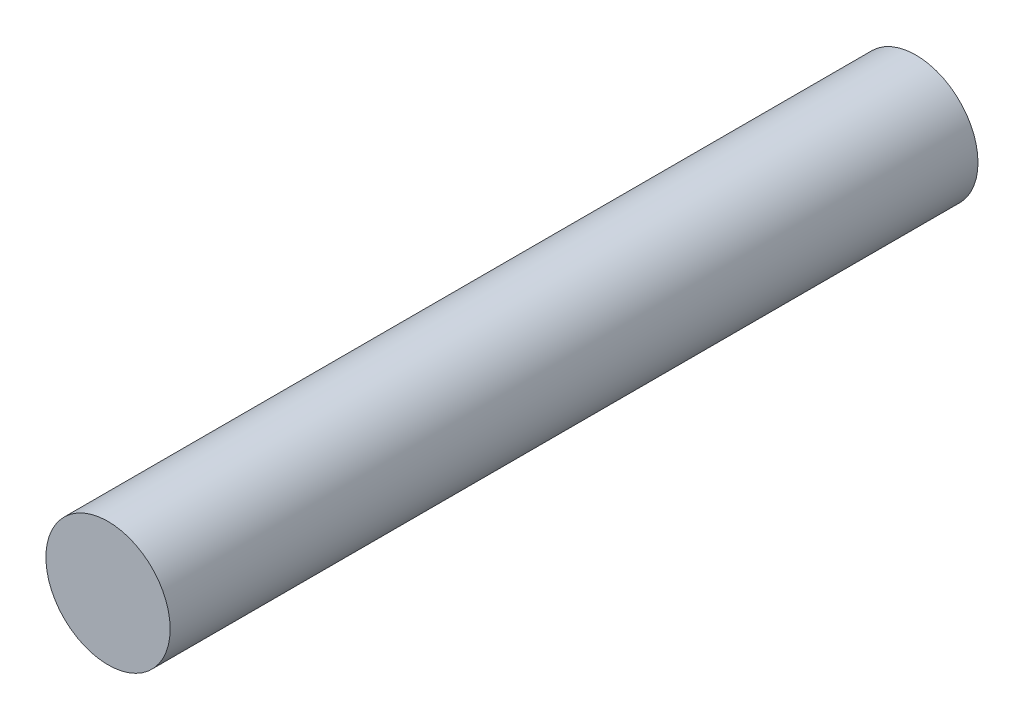
SolidWorks part; units mm, degrees
ref_plane "Front Plane" through (0, 0, 0) normal (0, 0, 1) x (1, 0, 0)
ref_plane "Top Plane" through (0, 0, 0) normal (0, 1, 0) x (1, 0, 0)
ref_plane "Right Plane" through (0, 0, 0) normal (1, 0, 0) x (0, 0, -1)
sketch "Sketch1" plane through (0, 0, 0) normal (0, 0, 1) x (1, 0, 0)
  circle A0 centre (0, 0) radius 3.175
extrude "Boss-Extrude1" add sketch "Sketch1" along normal blind 41.275
